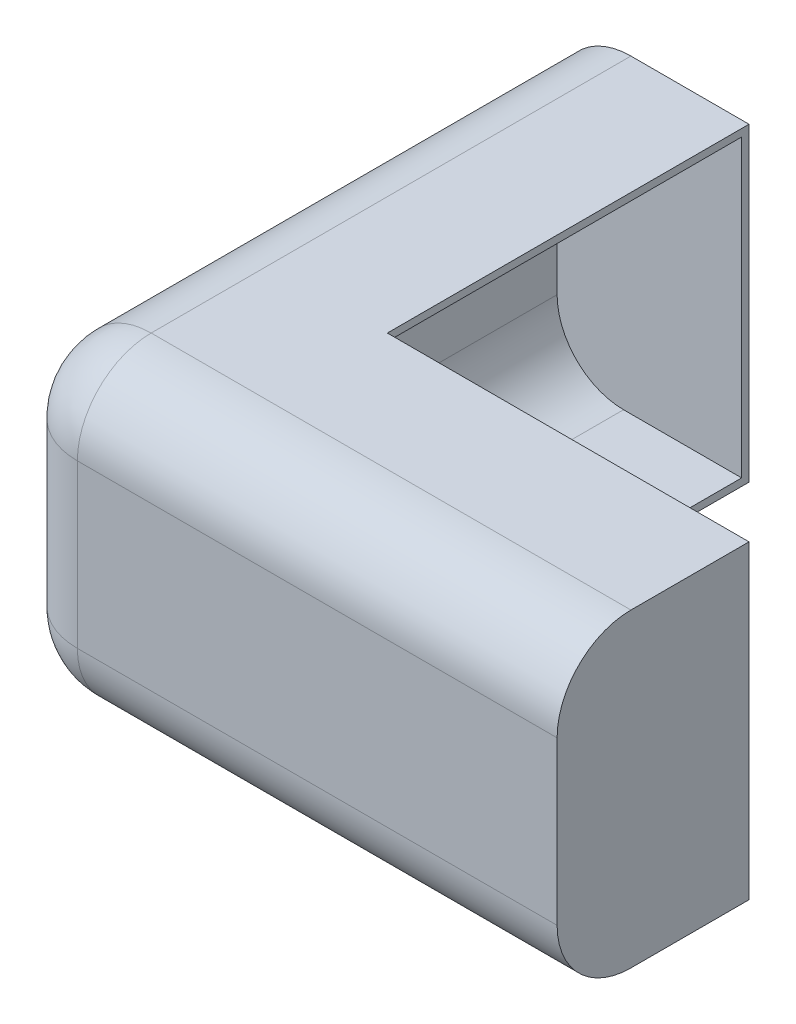
SolidWorks part; units mm, degrees
ref_plane "Front" through (0, 0, 0) normal (0, 0, 1) x (1, 0, 0)
ref_plane "Top" through (0, 0, 0) normal (0, 1, 0) x (1, 0, 0)
ref_plane "Right" through (0, 0, 0) normal (1, 0, 0) x (0, 0, -1)
sketch "Sketch1" plane through (0, 0, 0) normal (0, 1, 0) x (1, 0, 0)
  line L0 (0, 0) -> (0, 155.575)
  line L1 (0, 0) -> (155.575, 0)
  line L2 (-19.05, -19.05) -> (155.575, -19.05) construction
  line L3 (-19.05, -19.05) -> (-19.05, 155.575) construction
  line L4 (-82.55, -82.55) -> (155.575, -82.55)
  line L5 (-82.55, -82.55) -> (-82.55, 155.575)
  line L6 (0, 155.575) -> (-82.55, 155.575)
  line L7 (155.575, 0) -> (155.575, -82.55)
  dimension "D1" = 155.575
  dimension "D2" = 19.05
  dimension "D3" = 63.5
extrude "Boss-Extrude1" add sketch "Sketch1" along normal blind 133.35
fillet "Fillet1" radius 31.75 5 edges at (-82.55, 66.675, 82.55) (-82.55, 0, -36.5125) (-82.55, 133.35, -36.5125) (36.5125, 0, 82.55) (36.5125, 133.35, 82.55)
shell "Shell1" thickness 3.175
